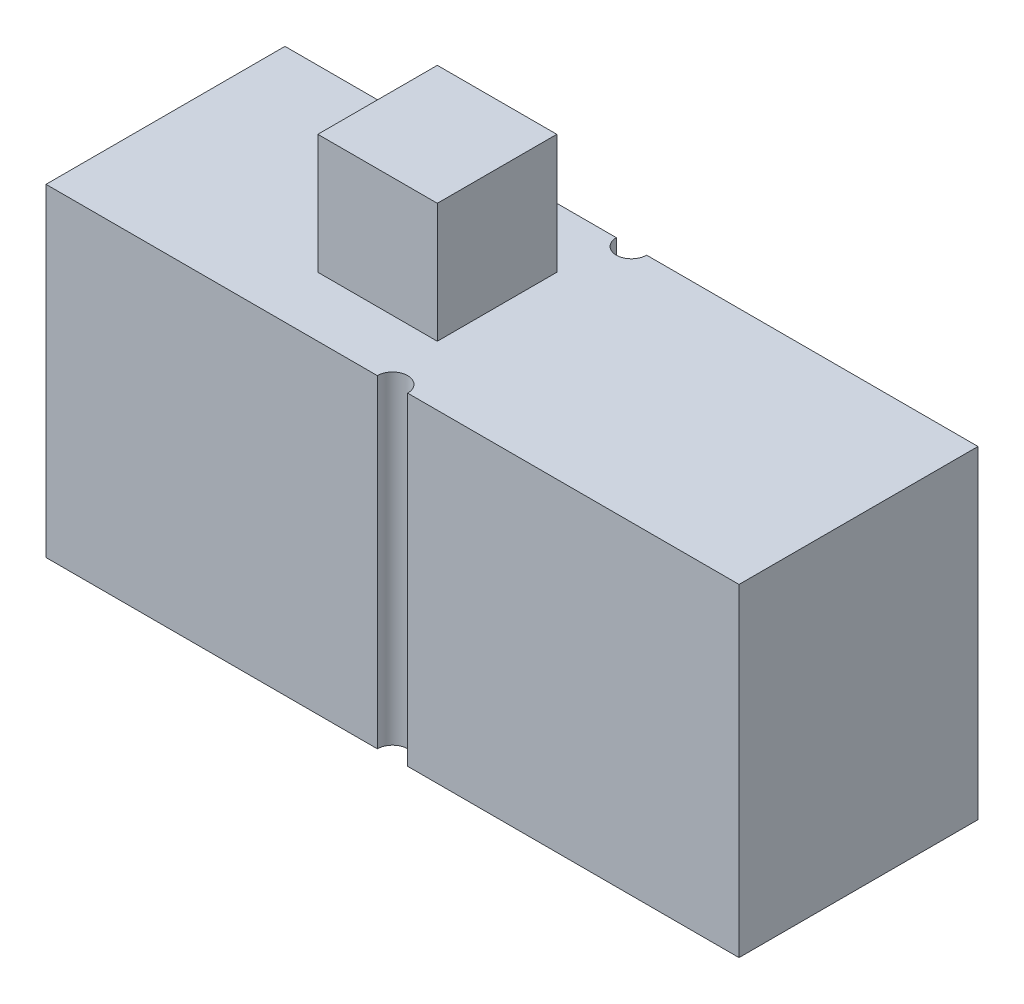
SolidWorks part; units mm, degrees
ref_plane "Front Plane" through (0, 0, 0) normal (0, 0, 1) x (1, 0, 0)
ref_plane "Top Plane" through (0, 0, 0) normal (0, 1, 0) x (1, 0, 0)
ref_plane "Right Plane" through (0, 0, 0) normal (1, 0, 0) x (0, 0, -1)
sketch "Sketch1" plane through (0, 0, 0) normal (0, 0, 1) x (1, 0, 0)
  line L1 (-5.8, -2.7051) -> (5.8, -2.7051)
  line L2 (-5.8, -2.7051) -> (-5.8, 2.7051)
  line L3 (-5.8, 2.7051) -> (5.8, 2.7051)
  line L4 (5.8, -2.7051) -> (5.8, 2.7051)
  line L5 (-5.8, -2.7051) -> (5.8, 2.7051) construction
  line L6 (-5.8, 2.7051) -> (5.8, -2.7051) construction
  point P0 (0, 0)
  dimension "D1" = 11.6
  dimension "D2" = 5.4102
extrude "Boss-Extrude1" add sketch "Sketch1" along normal blind 4
sketch "Sketch2" plane through (0, 2.7051, 0) normal (0, 1, 0) x (1, 0, 0)
  line L0 (-5.8, -2) -> (5.8, -2) construction
  line L1 (-2.25, -3) -> (2.25, -3) construction
  line L2 (-2.25, -3) -> (-2.25, -1) construction
  line L3 (-2.25, -1) -> (2.25, -1) construction
  line L4 (2.25, -3) -> (2.25, -1) construction
  line L5 (-2.25, -3) -> (2.25, -1) construction
  line L6 (-2.25, -1) -> (2.25, -3) construction
  line L7 (-5.8, -4) -> (-5.8, 0) construction
  line L8 (5.8, -4) -> (5.8, 0) construction
  line L10 (-2.25, -1) -> (-0.25, -1)
  line L11 (-2.25, -1) -> (-2.25, -3)
  line L12 (-2.25, -3) -> (-0.25, -3)
  line L13 (-0.25, -1) -> (-0.25, -3)
  point P0 (0, -2)
  dimension "D1" = 2
  dimension "D2" = 4.5
  dimension "D3" = 2
extrude "Boss-Extrude2" add sketch "Sketch2" along normal blind 2
sketch "Sketch3" plane through (0, 2.7051, 0) normal (0, 1, 0) x (1, 0, 0)
  line L0 (0, 0) -> (0, -4) construction
  line L1 (5.8, -4) -> (-5.8, -4) construction
  line L2 (-5.8, -2) -> (5.8, -2) construction
  line L3 (-5.8, -4) -> (-5.8, 0) construction
  line L4 (5.8, -4) -> (5.8, 0) construction
  line L5 (5.8, 0) -> (-5.8, 0) construction
  line L6 (-0.254, 0) -> (0.254, 0)
  line L8 (-0.254, -4) -> (0.254, -4)
  arc A0 (-0.254, 0) -> (0.254, 0) centre (0, 0) ccw
  arc A1 (-0.254, -4) -> (0.254, -4) centre (0, -4) cw
  dimension "D1" = 0.254
extrude "Cut-Extrude1" cut sketch "Sketch3" against normal through all both and the other way through all
